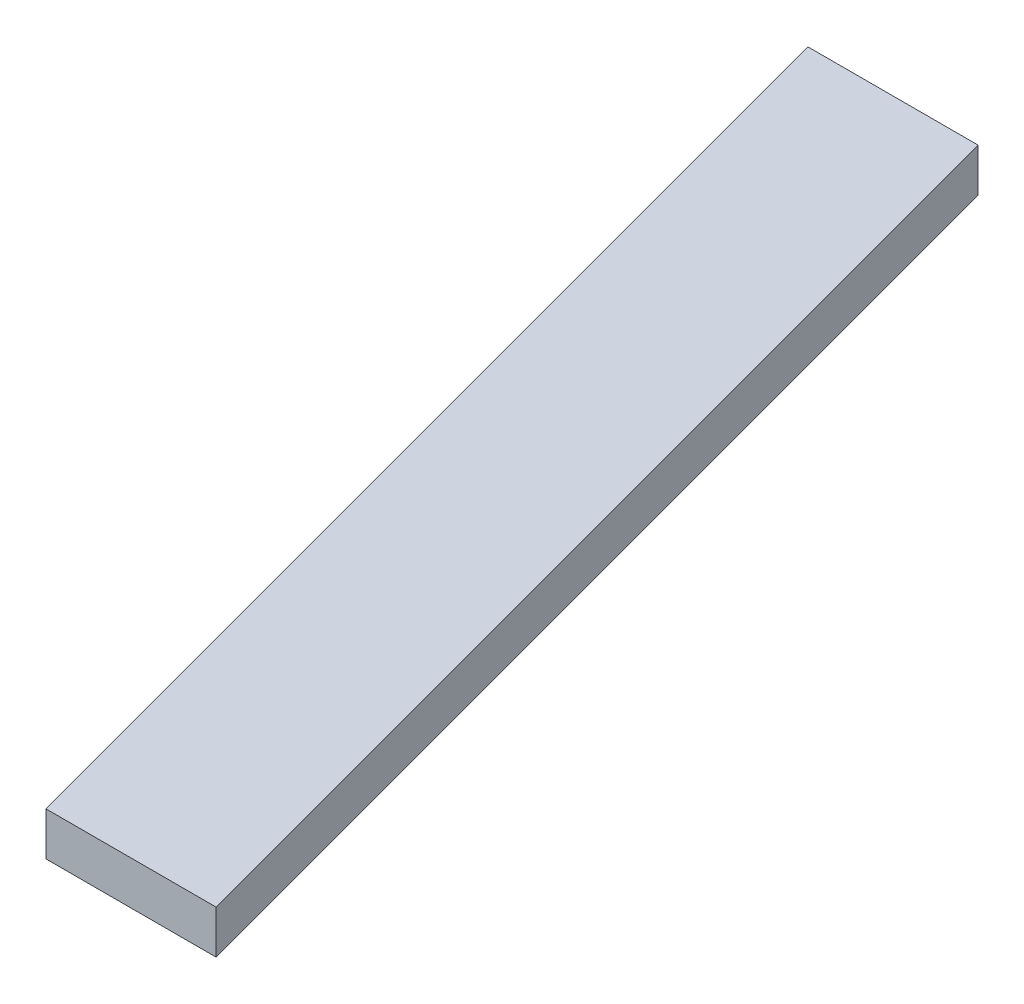
SolidWorks part; units mm, degrees
ref_plane "Front Plane" through (0, 0, 0) normal (0, 0, 1) x (1, 0, 0)
ref_plane "Top Plane" through (0, 0, 0) normal (0, 1, 0) x (1, 0, 0)
ref_plane "Right Plane" through (0, 0, 0) normal (1, 0, 0) x (0, 0, -1)
sketch "Sketch2" plane through (0, 0, 0) normal (0, 1, 0) x (1, 0, 0)
  line L0 (0, 0) -> (12.446, 0)
  line L1 (12.446, 0) -> (32.8637, -76.2)
  line L2 (32.8637, -76.2) -> (20.4177, -76.2)
  line L3 (20.4177, -76.2) -> (0, 0)
  dimension "D1" = 75
  dimension "D2" = 105
  dimension "D3" = 12.446
  dimension "D4" = 76.2
extrude "Boss-Extrude1" add sketch "Sketch2" along normal blind 3.175
